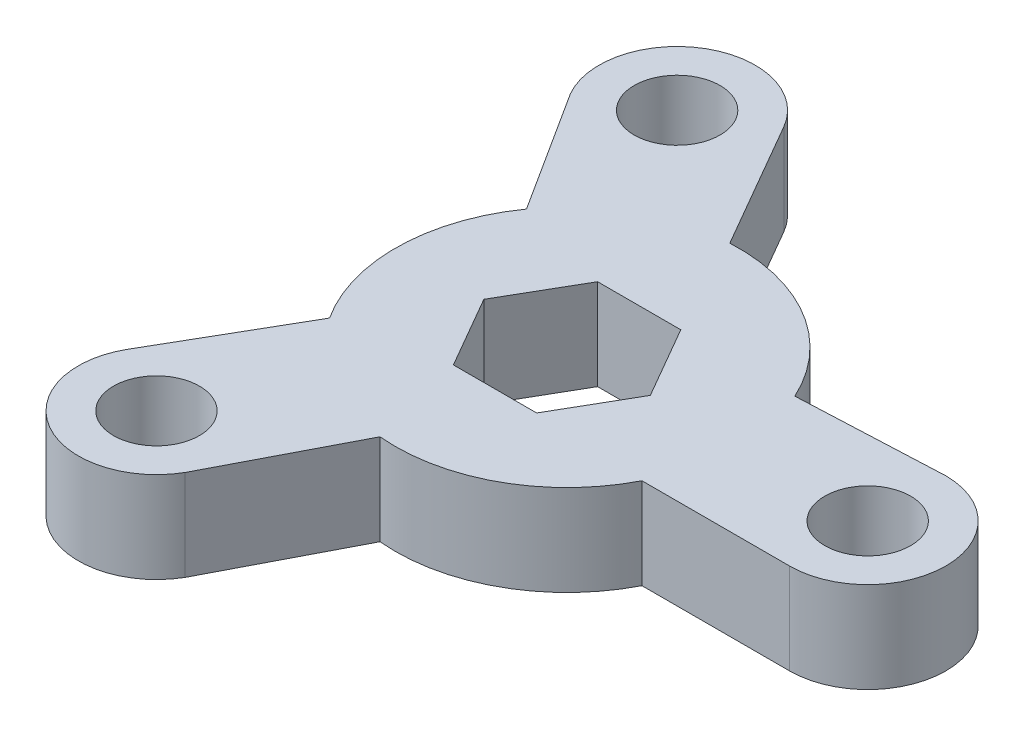
SolidWorks part; units mm, degrees
ref_plane "Front" through (0, 0, 0) normal (0, 0, 1) x (1, 0, 0)
ref_plane "Top" through (0, 0, 0) normal (0, 1, 0) x (1, 0, 0)
ref_plane "Right" through (0, 0, 0) normal (1, 0, 0) x (0, 0, -1)
sketch "Sketch1" plane through (0, 0, 0) normal (0, 1, 0) x (1, 0, 0)
  line L0 (2.5148, 0.2447) -> (13.0148, 0.2447)
  line L1 (2.5148, 0.2447) -> (-2.7352, 9.338)
  line L2 (2.5148, 0.2447) -> (-2.7352, -8.8486)
  line L3 (2.5148, 0.2447) -> (-2.7352, 9.338) construction
  line L10 (2.5148, 0.2447) -> (13.0148, 0.2447) construction
  line L11 (13.0148, -2.4841) -> (7.8583, -2.4841)
  line L12 (13.0148, 2.9736) -> (7.9691, 2.7447)
  line L13 (-5.0985, -7.4841) -> (-2.5203, -3.0185)
  line L14 (-0.372, -10.213) -> (1.9526, -5.7289)
  line L15 (-0.372, 10.7024) -> (2.2062, 6.2368)
  line L16 (-5.0985, 7.9736) -> (-2.3775, 3.7183)
  line L18 (1.0642, -2.2678) -> (3.9654, -2.2678)
  line L19 (3.9654, -2.2678) -> (5.4159, 0.2447)
  line L20 (5.4159, 0.2447) -> (3.9654, 2.7572)
  line L21 (3.9654, 2.7572) -> (1.0642, 2.7572)
  line L22 (1.0642, 2.7572) -> (-0.3864, 0.2447)
  line L23 (-0.3864, 0.2447) -> (1.0642, -2.2678)
  circle A0 centre (-2.7352, 9.338) radius 1.5
  circle A1 centre (13.0148, 0.2447) radius 1.5
  circle A2 centre (-2.7352, -8.8486) radius 1.5
  circle A3 centre (2.5148, 0.2447) radius 2.5125 construction
  arc A4 (-0.372, 10.7024) -> (-5.0985, 7.9736) centre (-2.7352, 9.338) ccw
  circle A5 centre (2.5148, 0.2447) radius 6
  arc A6 (13.0148, -2.4841) -> (13.0148, 2.9736) centre (13.0148, 0.2447) ccw
  arc A7 (-5.0985, -7.4841) -> (-0.372, -10.213) centre (-2.7352, -8.8486) ccw
  point P39 (2.5148, 0.2447)
  dimension "D1" = 3
  dimension "D3" = 3
extrude "Boss-Extrude1" add sketch "Sketch1" along normal blind 3.175
sketch "Sketch2" plane through (0, 3.175, 0) normal (0, 1, 0) x (1, 0, 0)
  line L1 (5.4217, 0.2447) -> (3.9682, 2.7622)
  line L2 (3.9682, 2.7622) -> (1.0613, 2.7622)
  line L3 (1.0613, 2.7622) -> (-0.3922, 0.2447)
  line L4 (-0.3922, 0.2447) -> (1.0613, -2.2728)
  line L5 (1.0613, -2.2728) -> (3.9682, -2.2728)
  line L6 (3.9682, -2.2728) -> (5.4217, 0.2447)
  circle A0 centre (2.5148, 0.2447) radius 2.5175 construction
  dimension "D1" = 5.035
extrude "Cut-Extrude1" cut sketch "Sketch2" against normal blind 10
